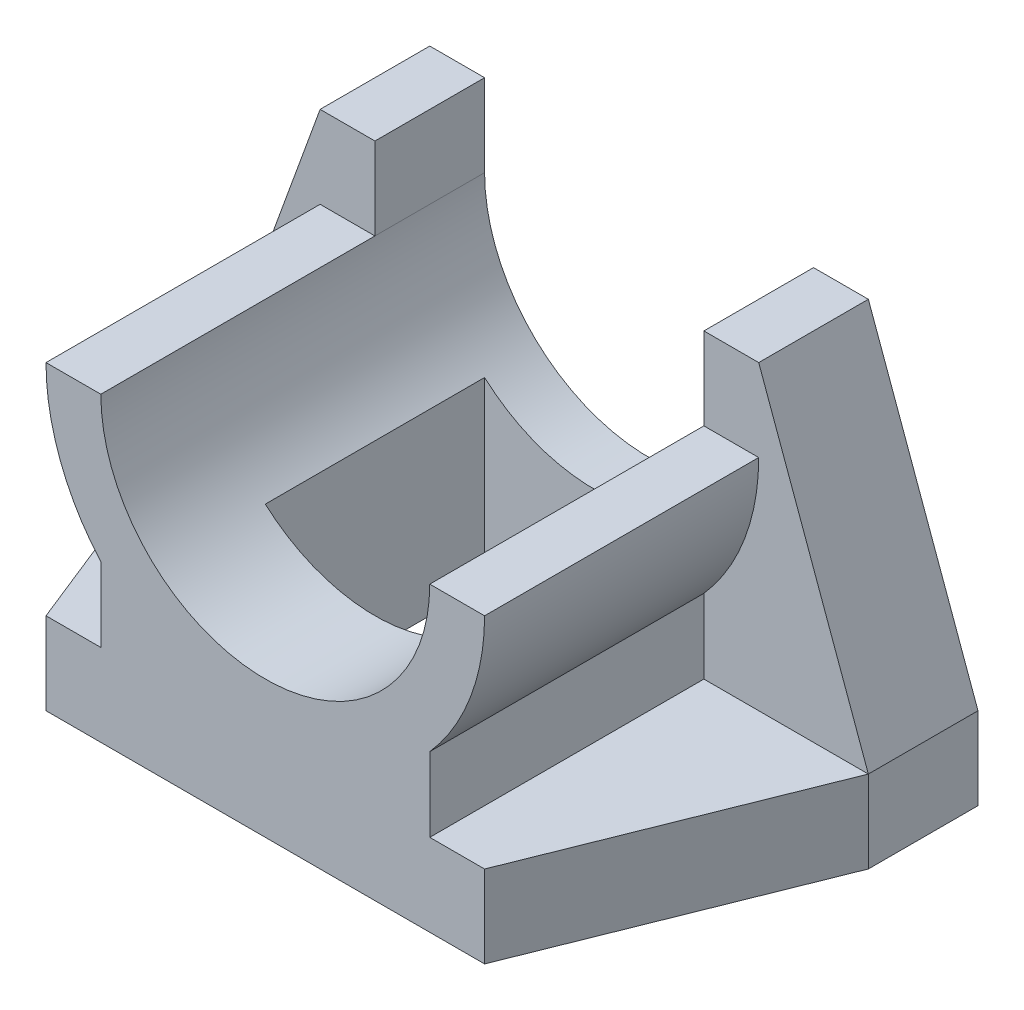
SolidWorks part; units mm, degrees
ref_plane "Front Plane" through (0, 0, 0) normal (0, 0, 1) x (1, 0, 0)
ref_plane "Top Plane" through (0, 0, 0) normal (0, 1, 0) x (1, 0, 0)
ref_plane "Right Plane" through (0, 0, 0) normal (1, 0, 0) x (0, 0, -1)
sketch "Sketch1" plane through (0, 0, 0) normal (0, 1, 0) x (1, 0, 0)
  line L1 (-40, 0) -> (40, 0)
  line L2 (-40, 0) -> (-40, -70)
  line L3 (-40, -70) -> (40, -70)
  line L4 (40, 0) -> (40, -70)
  dimension "D1" = 80
  dimension "D2" = 70
  dimension "D3" = 40
extrude "Boss-Extrude1" add sketch "Sketch1" along normal blind 15
sketch "Sketch2" plane through (0, 0, 0) normal (0, 0, 1) x (1, 0, 0)
  line L0 (-30, 10) -> (30, 10)
  line L1 (30, 10) -> (30, 28.5425)
  line L2 (40, 55) -> (-40, 55)
  line L3 (-30, 28.5425) -> (-30, 10)
  arc A0 (30, 28.5425) -> (40, 55) centre (0, 55) ccw
  arc A1 (-40, 55) -> (-30, 28.5425) centre (0, 55) ccw
  dimension "D1" = 80
  dimension "D2" = 60
  dimension "D3" = 55
  dimension "D4" = 30
extrude "Boss-Extrude2" add sketch "Sketch2" along normal blind 70
sketch "Sketch3" plane through (0, 0, 0) normal (0, 1, 0) x (1, 0, 0)
  line L0 (-60, 0) -> (-38, 0)
  line L1 (-38, 0) -> (-38, -70)
  line L2 (-38, -70) -> (-40, -70)
  line L3 (-40, -70) -> (-60, -20)
  line L4 (-60, -20) -> (-60, 0)
  dimension "D1" = 20
  dimension "D2" = 60
extrude "Boss-Extrude3" add sketch "Sketch3" along normal blind 15
sketch "Sketch4" plane through (0, 0, 0) normal (0, 0, 1) x (1, 0, 0)
  line L0 (-60, 15) -> (-30, 15)
  line L1 (-30, 15) -> (-30, 70)
  line L2 (-30, 70) -> (-40, 70)
  line L3 (-40, 70) -> (-60, 15)
  dimension "D1" = 10
  dimension "D2" = 30
  dimension "D3" = 70
  dimension "D4" = 15
  dimension "D5" = 30
extrude "Boss-Extrude4" add sketch "Sketch4" along normal blind 20
mirror "Mirror1" about plane through (0, 0, 0) normal (1, 0, 0) of "Boss-Extrude4", "Boss-Extrude3"
sketch "Sketch5" plane through (0, 0, 0) normal (0, 0, 1) x (1, 0, 0)
  line L0 (-30, 55) -> (30, 55)
  arc A0 (-30, 55) -> (30, 55) centre (0, 55) ccw
  dimension "D1" = 60
  dimension "D2" = 55
extrude "Cut-Extrude1" cut sketch "Sketch5" along normal through all
sketch "Sketch6" plane through (0, 0, 0) normal (0, 1, 0) x (1, 0, 0)
  line L1 (-20, -10) -> (20, -10)
  line L2 (-20, -10) -> (-20, -50)
  line L3 (-20, -50) -> (20, -50)
  line L4 (20, -10) -> (20, -50)
  dimension "D1" = 40
  dimension "D2" = 40
  dimension "D3" = 10
  dimension "D4" = 20
extrude "Cut-Extrude2" cut sketch "Sketch6" along normal through all
